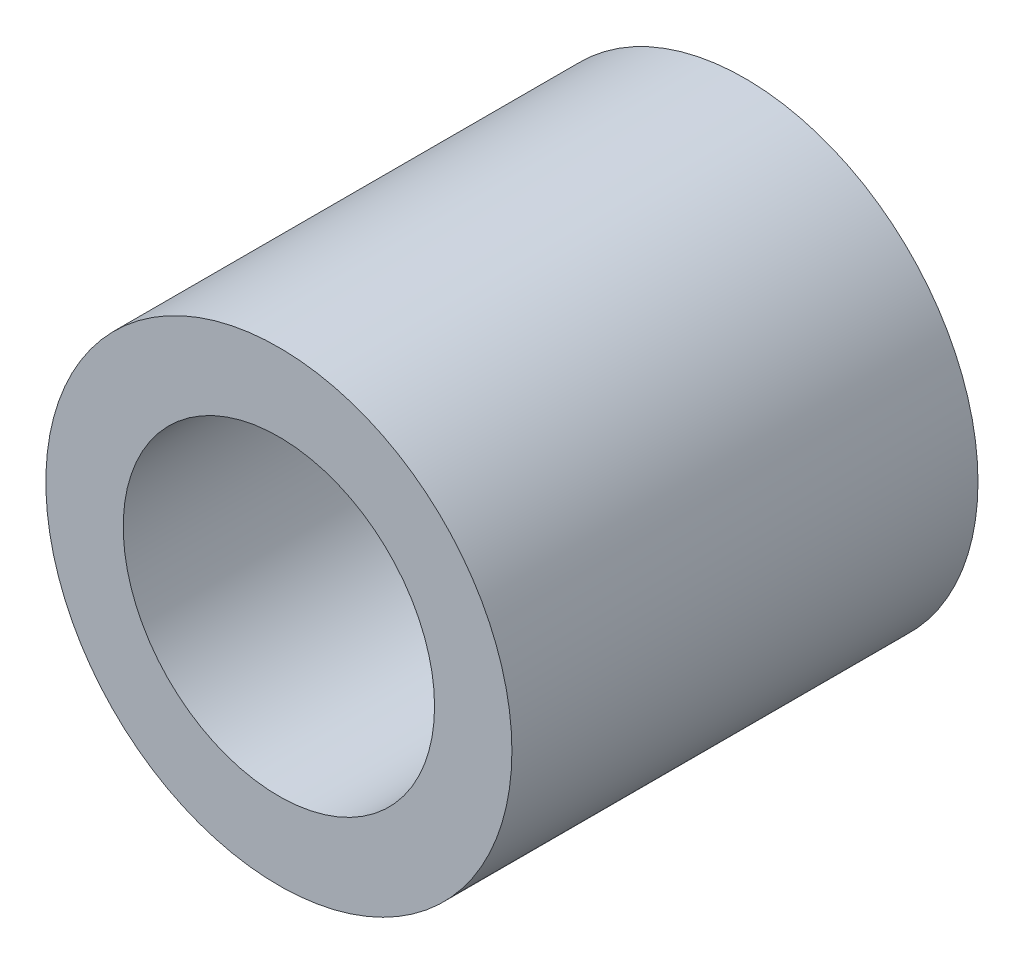
SolidWorks part; units mm, degrees
ref_plane "Plan de face" through (0, 0, 0) normal (0, 0, 1) x (1, 0, 0)
ref_plane "Plan de dessus" through (0, 0, 0) normal (0, 1, 0) x (1, 0, 0)
ref_plane "Plan de droite" through (0, 0, 0) normal (1, 0, 0) x (0, 0, -1)
sketch "Sketch1" plane through (0, 0, 0) normal (0, 0, 1) x (1, 0, 0)
  circle A0 centre (0, 0) radius 1.25
  circle A1 centre (0, 0) radius 0.835
  dimension "D1" = 2.5
  dimension "D2" = 1.67
extrude "Boss-Extrude1" add sketch "Sketch1" along normal blind 2.5
